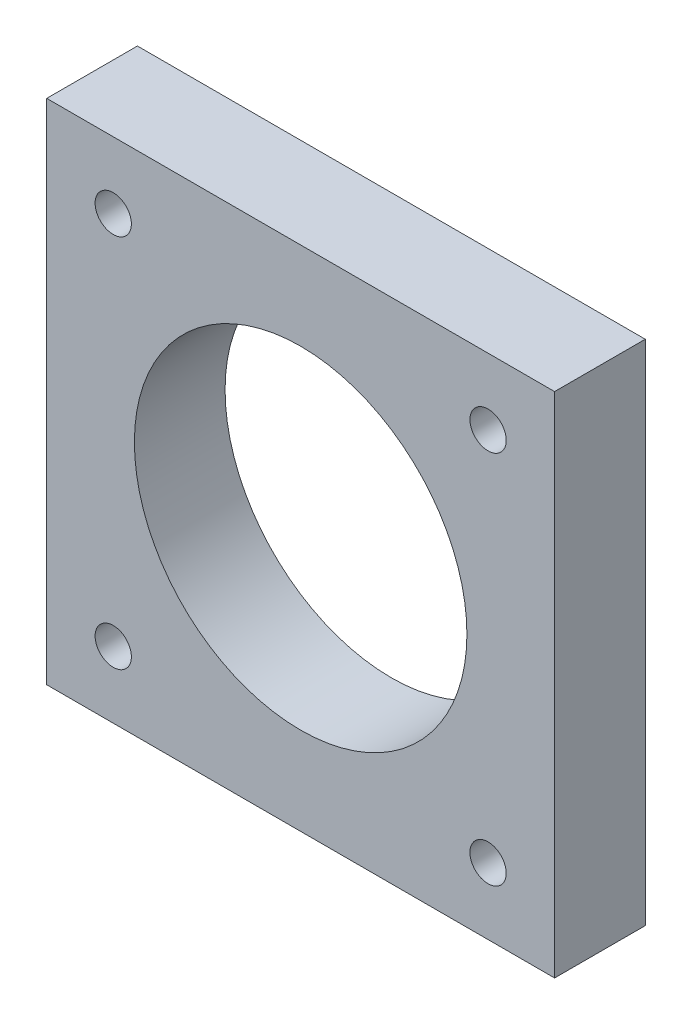
SolidWorks part; units mm, degrees
material "ABS"
ref_plane "Front Plane" through (0, 0, 0) normal (0, 0, 1) x (1, 0, 0)
ref_plane "Top Plane" through (0, 0, 0) normal (0, 1, 0) x (1, 0, 0)
ref_plane "Right Plane" through (0, 0, 0) normal (1, 0, 0) x (0, 0, -1)
sketch "Sketch1" plane through (0, 0, 0) normal (0, 0, 1) x (1, 0, 0)
  line L0 (21, 5.5) -> (21, 0) construction
  line L1 (0, 0) -> (42, 0)
  line L2 (0, 0) -> (0, 42)
  line L3 (0, 42) -> (42, 42)
  line L4 (42, 0) -> (42, 42)
  line L5 (5.5, 5.5) -> (36.5, 5.5) construction
  line L6 (5.5, 5.5) -> (5.5, 36.5) construction
  line L7 (5.5, 36.5) -> (36.5, 36.5) construction
  line L8 (36.5, 5.5) -> (36.5, 36.5) construction
  line L9 (5.5, 21) -> (0, 21) construction
  line L10 (36.5, 5.5) -> (5.5, 36.5) construction
  circle A0 centre (5.5, 5.5) radius 1.5
  circle A1 centre (36.5, 5.5) radius 1.5
  circle A2 centre (36.5, 36.5) radius 1.5
  circle A3 centre (5.5, 36.5) radius 1.5
  circle A4 centre (21, 21) radius 13.75
  point P19 (35.4393, 6.5607)
  point P20 (30.7227, 11.2773)
  point P21 (21, 7.25)
  dimension "D3" = 3
  dimension "D4" = 1.75
  dimension "D1" = 42
  dimension "D2" = 31
extrude "Boss-Extrude1" add sketch "Sketch1" along normal blind 7.5
